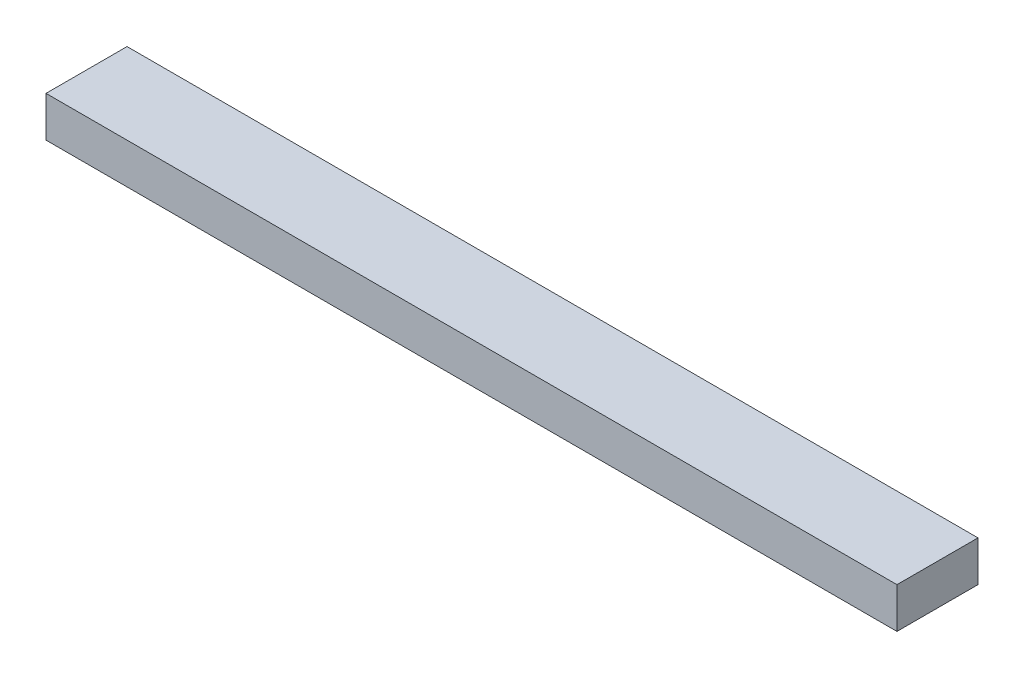
SolidWorks part; units mm, degrees
material "Plain Carbon Steel"
ref_plane "Front Plane" through (0, 0, 0) normal (0, 0, 1) x (1, 0, 0)
ref_plane "Top Plane" through (0, 0, 0) normal (0, 1, 0) x (1, 0, 0)
ref_plane "Right Plane" through (0, 0, 0) normal (1, 0, 0) x (0, 0, -1)
sketch "Sketch1" plane through (0, 0, 0) normal (1, 0, 0) x (0, 0, -1)
  line L0 (190.5, 25.4) -> (241.3, 25.4) construction
  line L1 (241.3, 50.8) -> (190.5, 50.8) construction
  line L2 (241.3, 50.8) -> (241.3, 25.4) construction
  line L3 (190.5, 50.8) -> (190.5, 25.4) construction
  line L4 (190.5, 25.4) -> (241.3, 25.4)
  line L5 (241.3, 50.8) -> (190.5, 50.8)
  line L6 (241.3, 50.8) -> (241.3, 25.4)
  line L7 (190.5, 50.8) -> (190.5, 25.4)
extrude "Boss-Extrude1" add sketch "Sketch1" along normal up to vertex (266.7 mm away) and the other way up to vertex (266.7 mm away)
